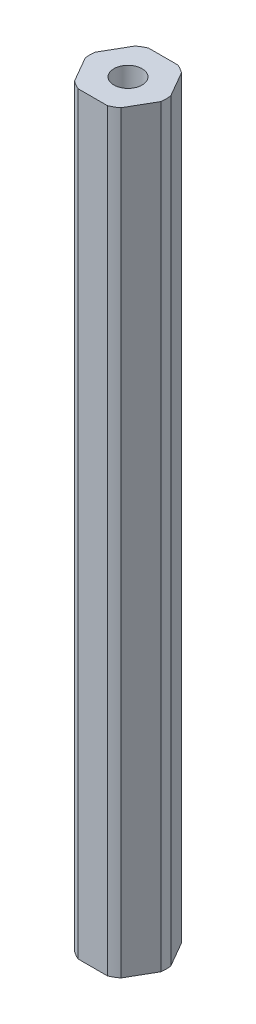
SolidWorks part; units mm, degrees
material "6061-T6 (SS)"
ref_plane "Front" through (0, 0, 0) normal (0, 0, 1) x (1, 0, 0)
ref_plane "Top" through (0, 0, 0) normal (0, 1, 0) x (1, 0, 0)
ref_plane "Right" through (0, 0, 0) normal (1, 0, 0) x (0, 0, -1)
sketch "Sketch1" plane through (0, 0, 0) normal (0, 1, 0) x (1, 0, 0)
  line L1 (3.6662, -6.35) -> (7.3323, 0)
  line L2 (7.3323, 0) -> (3.6662, 6.35)
  line L3 (3.6662, 6.35) -> (-3.6662, 6.35)
  line L4 (-3.6662, 6.35) -> (-7.3323, 0)
  line L5 (-7.3323, 0) -> (-3.6662, -6.35)
  line L6 (-3.6662, -6.35) -> (3.6662, -6.35)
  circle A0 centre (0, 0) radius 6.35 construction
  circle A1 centre (0, 0) radius 6.8758
  circle A2 centre (0, 0) radius 2.5527
  dimension "D2" = 13.7516
  dimension "D3" = 5.1054
  dimension "D1" = 12.7
extrude "Boss-Extrude1" add sketch "Sketch1" along normal mid plane 135.89 contours L6 A1 L1 L2 L3 L4 L5 A2
